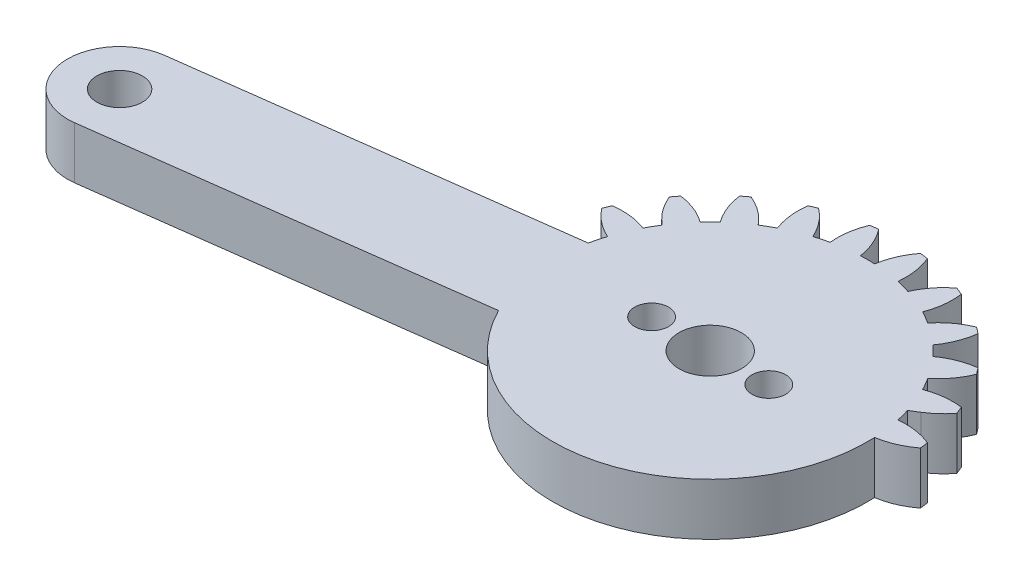
SolidWorks part; units mm, degrees
ref_plane "Front Plane" through (0, 0, 0) normal (0, 0, 1) x (1, 0, 0)
ref_plane "Top Plane" through (0, 0, 0) normal (0, 1, 0) x (1, 0, 0)
ref_plane "Right Plane" through (0, 0, 0) normal (1, 0, 0) x (0, 0, -1)
ref_plane "Plane1" through (0, 4, 0) normal (0, 1, 0) x (1, 0, 0)
sketch "Sketch1" plane through (0, 4, 0) normal (0, 1, 0) x (1, 0, 0)
  line L0 (1.4381, 3.6001) -> (2.0816, 4)
  line L1 (-21.9429, 2.4762) -> (-50.6948, -1.309)
  line L2 (-49.6505, -9.2406) -> (-20.8986, -5.4553)
  circle A0 centre (-50.1726, -5.2748) radius 1.75
  arc A1 (4.3495, 2.2179) -> (1.7031, 2.6025) centre (2.274, -2.7673) ccw
  arc A2 (1.7031, 2.6025) -> (1.4381, 3.6001) centre (-10.1063, 0) ccw
  arc A3 (2.0816, 4) -> (3.5217, 5.3071) centre (-0.7683, 8.5867) ccw
  arc A4 (3.5217, 5.3071) -> (3.2829, 5.8838) centre (-10.1063, 0) ccw
  arc A5 (3.2829, 5.8838) -> (0.6271, 5.5703) centre (2.5684, 0.5313) ccw
  arc A6 (0.6271, 5.5703) -> (0.0844, 6.5103) centre (-10.1063, 0) ccw
  arc A7 (0.0844, 6.5103) -> (1.6838, 8.6535) centre (-3.3089, 10.711) ccw
  arc A8 (1.6838, 8.6535) -> (1.3038, 9.1487) centre (-10.1063, 0) ccw
  arc A9 (1.3038, 9.1487) -> (-1.1803, 8.1585) centre (1.999, 3.7936) ccw
  arc A10 (-1.1803, 8.1585) -> (-1.9479, 8.926) centre (-10.1063, 0) ccw
  arc A11 (-1.9479, 8.926) -> (-0.9576, 11.4102) centre (-6.3127, 12.1053) ccw
  arc A12 (-0.9576, 11.4102) -> (-1.4528, 11.7901) centre (-10.1063, 0) ccw
  arc A13 (-1.4528, 11.7901) -> (-3.596, 10.1907) centre (0.6046, 6.7975) ccw
  arc A14 (-3.596, 10.1907) -> (-4.5361, 10.7334) centre (-10.1063, 0) ccw
  arc A15 (-4.5361, 10.7334) -> (-4.2225, 13.3892) centre (-9.5751, 12.6747) ccw
  arc A16 (-4.2225, 13.3892) -> (-4.7992, 13.6281) centre (-10.1063, 0) ccw
  arc A17 (-4.7992, 13.6281) -> (-6.4554, 11.5285) centre (-1.5196, 9.3381) ccw
  arc A18 (-6.4554, 11.5285) -> (-7.5039, 11.8094) centre (-10.1063, 0) ccw
  arc A19 (-7.5039, 11.8094) -> (-7.8884, 14.4558) centre (-12.8736, 12.3803) ccw
  arc A20 (-7.8884, 14.4558) -> (-8.5072, 14.5373) centre (-10.1063, 0) ccw
  arc A21 (-8.5072, 14.5373) -> (-9.5636, 12.0806) centre (-4.2291, 11.2423) ccw
  arc A22 (-9.5636, 12.0806) -> (-10.6491, 12.0806) centre (-10.1063, 0) ccw
  arc A23 (-10.6491, 12.0806) -> (-11.7054, 14.5373) centre (-15.9836, 11.2423) ccw
  arc A24 (-11.7054, 14.5373) -> (-12.3243, 14.4558) centre (-10.1063, 0) ccw
  arc A25 (-12.3243, 14.4558) -> (-12.7088, 11.8094) centre (-7.3391, 12.3803) ccw
  arc A26 (-12.7088, 11.8094) -> (-13.7573, 11.5285) centre (-10.1063, 0) ccw
  arc A27 (-13.7573, 11.5285) -> (-15.4135, 13.6281) centre (-18.6931, 9.3381) ccw
  arc A28 (-15.4135, 13.6281) -> (-15.9901, 13.3892) centre (-10.1063, 0) ccw
  arc A29 (-15.9901, 13.3892) -> (-15.6766, 10.7334) centre (-10.6376, 12.6747) ccw
  arc A30 (-15.6766, 10.7334) -> (-16.6166, 10.1907) centre (-10.1063, 0) ccw
  arc A31 (-16.6166, 10.1907) -> (-18.7599, 11.7901) centre (-20.8173, 6.7975) ccw
  arc A32 (-18.7599, 11.7901) -> (-19.255, 11.4102) centre (-10.1063, 0) ccw
  arc A33 (-19.255, 11.4102) -> (-18.2648, 8.926) centre (-13.9, 12.1053) ccw
  arc A34 (-18.2648, 8.926) -> (-19.0324, 8.1585) centre (-10.1063, 0) ccw
  arc A35 (-19.0324, 8.1585) -> (-21.5165, 9.1487) centre (-22.2117, 3.7936) ccw
  arc A36 (-21.5165, 9.1487) -> (-21.8965, 8.6535) centre (-10.1063, 0) ccw
  arc A37 (-21.8965, 8.6535) -> (-20.2971, 6.5103) centre (-16.9038, 10.711) ccw
  arc A38 (-20.2971, 6.5103) -> (-20.8398, 5.5703) centre (-10.1063, 0) ccw
  arc A39 (-20.8398, 5.5703) -> (-23.4956, 5.8838) centre (-22.7811, 0.5313) ccw
  arc A40 (-23.4956, 5.8838) -> (-23.7344, 5.3071) centre (-10.1063, 0) ccw
  arc A41 (-23.7344, 5.3071) -> (-21.6348, 3.6509) centre (-19.4444, 8.5867) ccw
  arc A42 (-21.6348, 3.6509) -> (-21.9429, 2.4762) centre (-10.1063, 0) ccw
  arc A43 (-50.6948, -1.309) -> (-49.6505, -9.2406) centre (-50.1726, -5.2748) ccw
  arc A44 (-20.8986, -5.4553) -> (1.9742, 0.5427) centre (-10.1063, 0) ccw
  arc A45 (1.9742, 0.5427) -> (4.431, 1.5991) centre (1.1359, 5.8773) ccw
  arc A46 (4.431, 1.5991) -> (4.3495, 2.2179) centre (-10.1063, 0) ccw
  circle A47 centre (-10.1063, 0) radius 2.4
  circle A48 centre (-5.6063, 0) radius 1.3
  circle A49 centre (-14.6063, 0) radius 1.3
  dimension "D1" = 3.5
  dimension "D2" = 4.8
  dimension "D3" = 2.6
  dimension "D4" = 5.4
  dimension "D5" = 12.0927
  dimension "D6" = 14.625
  dimension "D7" = 4
  dimension "D8" = 0.0844
  dimension "D9" = 0.6046
  dimension "D10" = 0.6271
  dimension "D11" = 1.1359
  dimension "D12" = 1.3038
  dimension "D13" = 1.4381
  dimension "D14" = 1.7031
  dimension "D15" = 1.9742
  dimension "D16" = 1.999
  dimension "D17" = 2.0816
  dimension "D18" = 2.274
  dimension "D19" = 2.5684
  dimension "D20" = 0.7683
  dimension "D21" = 1.4528
  dimension "D22" = 1.9479
  dimension "D23" = 8.5072
  dimension "D24" = 9.5636
  dimension "D25" = 9.5751
  dimension "D26" = 10.1063
  dimension "D27" = 20.8986
  dimension "D28" = 21.9429
  dimension "D37" = 5.6063
  dimension "D55" = 14.6063
extrude "Boss-Extrude1" add sketch "Sketch1" against normal blind 4
